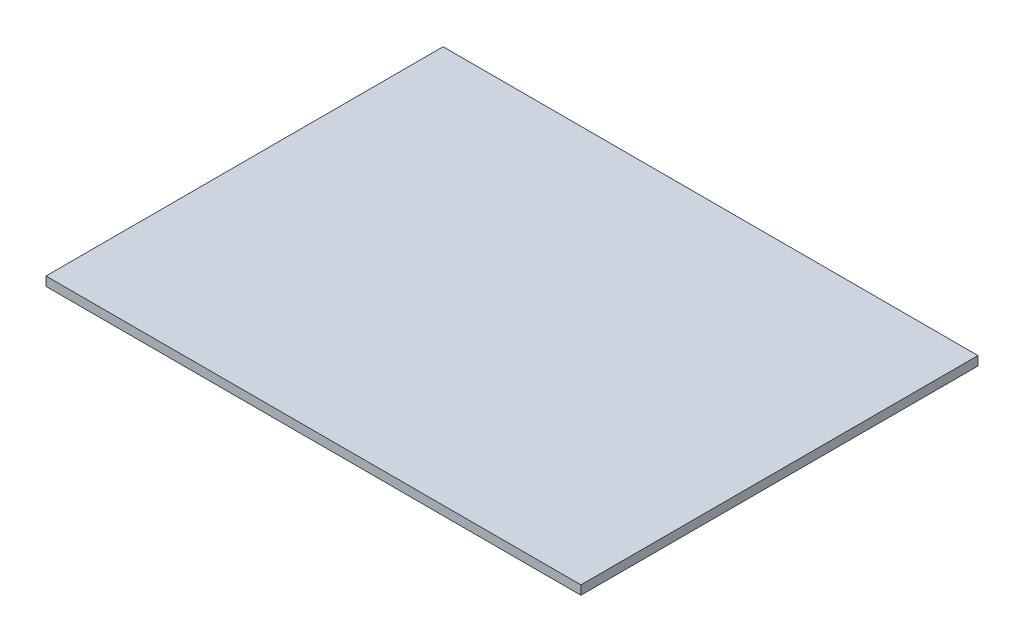
SolidWorks part; units mm, degrees
ref_plane "Front Plane" through (0, 0, 0) normal (0, 0, 1) x (1, 0, 0)
ref_plane "Top Plane" through (0, 0, 0) normal (0, 1, 0) x (1, 0, 0)
ref_plane "Right Plane" through (0, 0, 0) normal (1, 0, 0) x (0, 0, -1)
sketch "Sketch1" plane through (0, 0, 0) normal (0, 1, 0) x (1, 0, 0)
  line L1 (45.847, -34.036) -> (-45.847, -34.036)
  line L2 (45.847, -34.036) -> (45.847, 34.036)
  line L3 (45.847, 34.036) -> (-45.847, 34.036)
  line L4 (-45.847, -34.036) -> (-45.847, 34.036)
  line L5 (45.847, -34.036) -> (-45.847, 34.036) construction
  line L6 (45.847, 34.036) -> (-45.847, -34.036) construction
  point P0 (0, 0)
  dimension "D1" = 91.694
  dimension "D2" = 68.072
extrude "Boss-Extrude1" add sketch "Sketch1" along normal blind 1.5494
